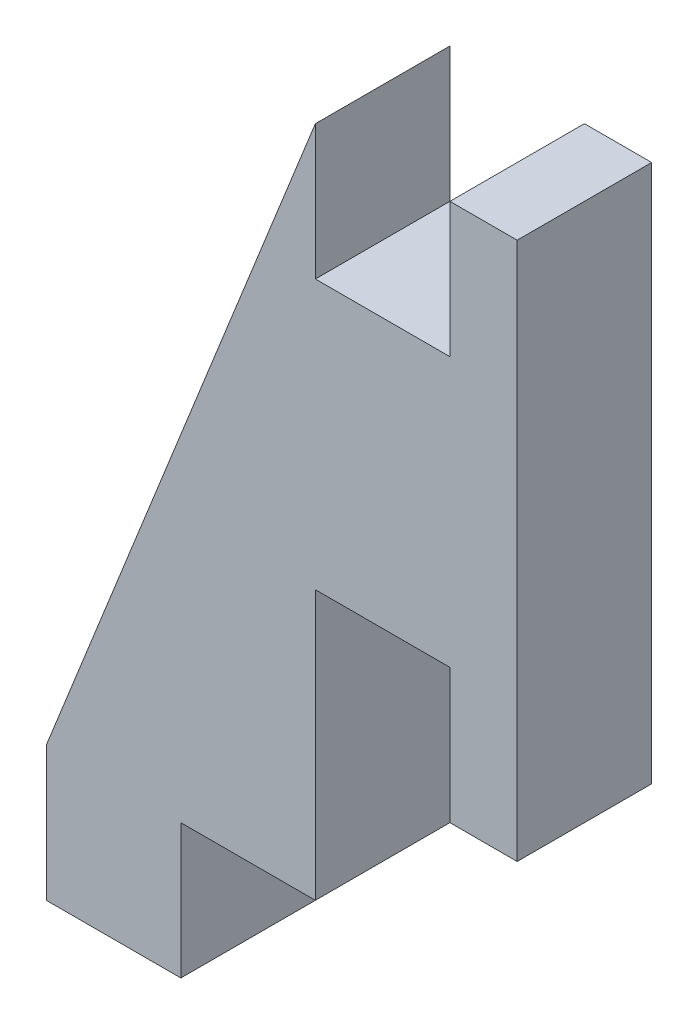
SolidWorks part; units mm, degrees
ref_plane "Front Plane" through (0, 0, 0) normal (0, 0, 1) x (1, 0, 0)
ref_plane "Top Plane" through (0, 0, 0) normal (0, 1, 0) x (1, 0, 0)
ref_plane "Right Plane" through (0, 0, 0) normal (1, 0, 0) x (0, 0, -1)
sketch "Sketch1" plane through (0, 0, 0) normal (0, 0, 1) x (1, 0, 0)
  line L0 (0, 0) -> (0, 12.7)
  line L1 (0, 0) -> (-6.35, 0)
  line L2 (-6.35, 0) -> (-6.35, -6.35)
  line L3 (-6.35, -6.35) -> (-12.7, -6.35)
  line L4 (-12.7, -6.35) -> (-12.7, 0)
  line L6 (-12.7, 0) -> (0, 31.75)
  line L7 (0, 12.7) -> (6.35, 12.7)
  line L8 (6.35, 12.7) -> (6.35, 25.4)
  line L9 (6.35, 25.4) -> (0, 25.4)
  line L10 (0, 25.4) -> (0, 31.75)
  point P3 (1.0955, 29.0321)
  point P8 (0, 0)
  point P13 (0.6685, 31.8687)
  point P14 (0, 0)
  point P15 (0, 0)
  point P16 (-13.1735, 0)
  point P17 (0, 0)
  dimension "D1" = 12.7
  dimension "D2" = 12.7
  dimension "D3" = 6.35
  dimension "D4" = 31.75
  dimension "D5" = 6.35
  dimension "D6" = 6.35
  dimension "D8" = 6.35
extrude "Boss-Extrude1" add sketch "Sketch1" along normal blind 6.35
sketch "Sketch2" plane through (0, 0, 0) normal (0, 0, 1) x (1, 0, 0)
  line L0 (6.35, 12.7) -> (6.35, 25.4) construction
  line L1 (9.525, 6.35) -> (6.35, 6.35)
  line L2 (9.525, 6.35) -> (9.525, 31.75)
  line L3 (9.525, 31.75) -> (6.35, 31.75)
  line L4 (6.35, 6.35) -> (6.35, 31.75)
  line L5 (7.9375, 31.75) -> (7.9375, 6.35) construction
  line L6 (9.525, 19.05) -> (6.35, 19.05) construction
  point P0 (7.9375, 19.05)
  point P4 (0, 0)
  point P5 (0, 0)
  point P8 (6.35, 19.05)
  point P9 (9.525, 30.9318)
  dimension "D1" = 3.175
  dimension "D2" = 25.4
extrude "Boss-Extrude2" add sketch "Sketch2" along normal blind 6.35
